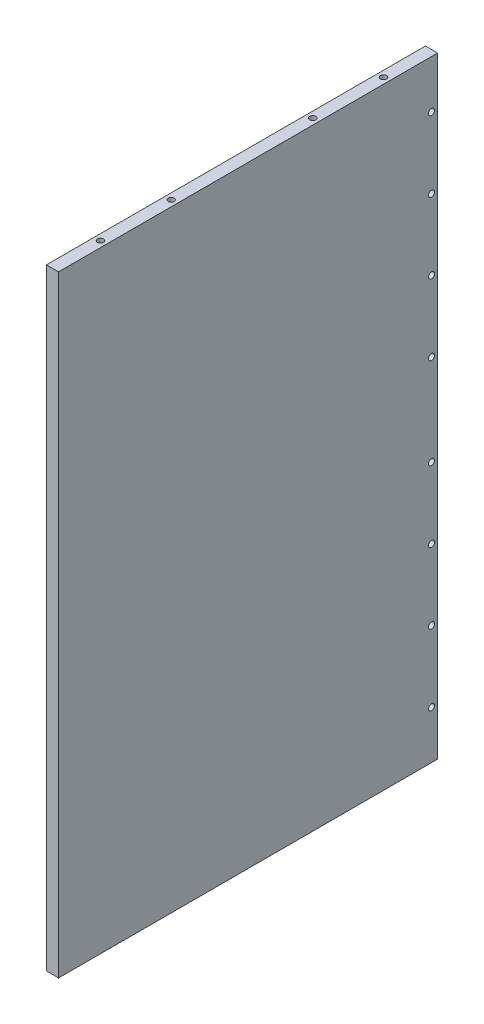
SolidWorks part; units mm, degrees
ref_plane "Alzado" through (0, 0, 0) normal (0, 0, 1) x (1, 0, 0)
ref_plane "Planta" through (0, 0, 0) normal (0, 1, 0) x (1, 0, 0)
ref_plane "Vista lateral" through (0, 0, 0) normal (1, 0, 0) x (0, 0, -1)
sketch "Croquis2" plane through (0, 0, 0) normal (1, 0, 0) x (0, 0, -1)
  line L1 (-187.5, 302.5) -> (187.5, 302.5)
  line L2 (-187.5, 302.5) -> (-187.5, -302.5)
  line L3 (-187.5, -302.5) -> (187.5, -302.5)
  line L4 (187.5, 302.5) -> (187.5, -302.5)
  dimension "D1" = 375
  dimension "D2" = 605
  dimension "D3" = 302.5
  dimension "D4" = 187.5
extrude "Saliente-Extruir1" add sketch "Croquis2" along normal mid plane 12
sketch "Croquis3" plane through (0, 302.5, 0) normal (0, 1, 0) x (1, 0, 0)
  line L0 (0, 187.5) -> (0, -187.5) construction
  line L1 (6, 187.5) -> (-6, 187.5) construction
  line L2 (6, -187.5) -> (-6, -187.5) construction
  line L3 (-6, 0) -> (6, 0) construction
  line L4 (-6, 187.5) -> (-6, -187.5) construction
  line L5 (6, 187.5) -> (6, -187.5) construction
  circle A0 centre (0, 140) radius 3
  circle A1 centre (0, 70) radius 3
  circle A2 centre (0, -70) radius 3
  circle A3 centre (0, -140) radius 3
  dimension "D1" = 47.5
  dimension "D2" = 2
extrude "Cortar-Extruir1" cut sketch "Croquis3" against normal blind 12
mirror "Simetría1" about plane through (0, 0, 0) normal (0, 1, 0) of "Cortar-Extruir1"
sketch "Croquis6" plane through (6, 0, 0) normal (1, 0, 0) x (0, 0, -1)
  line L0 (181.5, 302.5) -> (181.5, -302.5) construction
  line L1 (187.5, 302.5) -> (-187.5, 302.5) construction
  line L2 (-187.5, -302.5) -> (187.5, -302.5) construction
  line L3 (187.5, -302.5) -> (187.5, 302.5) construction
  line L4 (-187.5, 0) -> (187.5, 0) construction
  line L5 (-187.5, 302.5) -> (-187.5, -302.5) construction
  circle A0 centre (181.5, -255) radius 3
  circle A1 centre (181.5, -185) radius 3
  circle A2 centre (181.5, -115) radius 3
  circle A3 centre (181.5, -45) radius 3
  circle A4 centre (181.5, 45) radius 3
  circle A5 centre (181.5, 115) radius 3
  circle A6 centre (181.5, 185) radius 3
  circle A7 centre (181.5, 255) radius 3
  dimension "D2" = 47.5
  dimension "D1" = 6
  dimension "D3" = 4
extrude "Cortar-Extruir2" cut sketch "Croquis6" against normal blind 5
